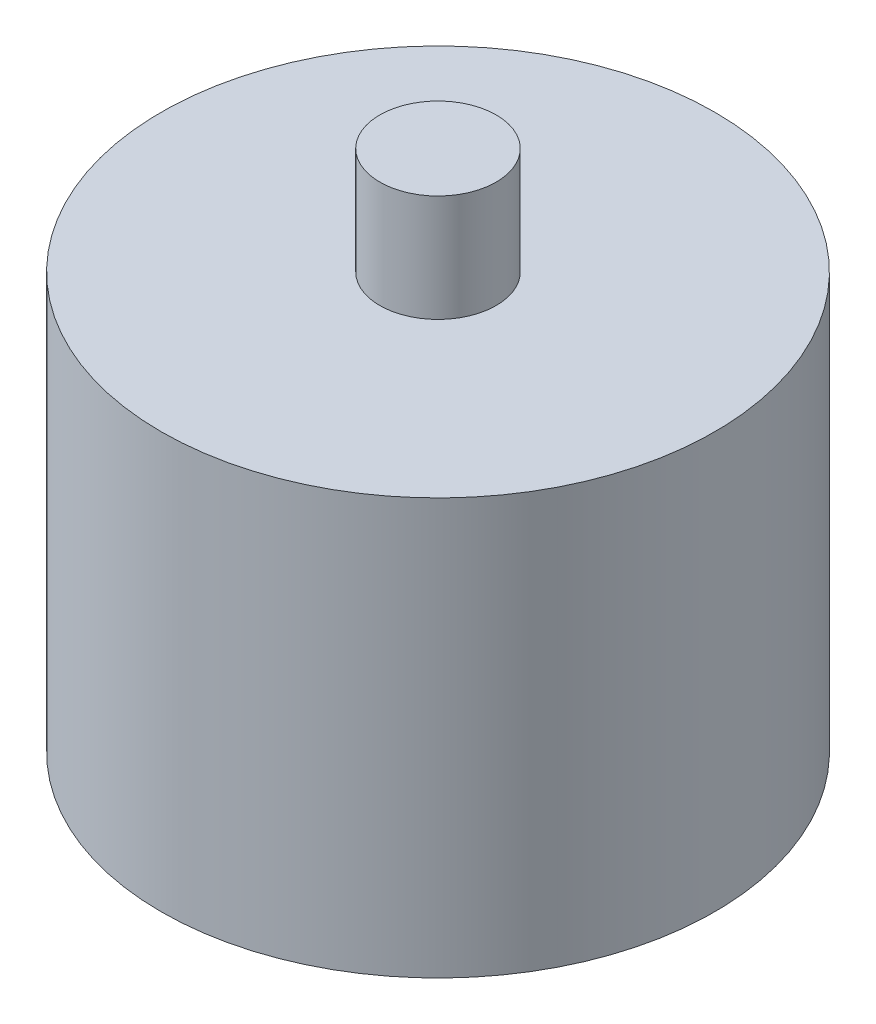
SolidWorks part; units mm, degrees
ref_plane "Front Plane" through (0, 0, 0) normal (0, 0, 1) x (1, 0, 0)
ref_plane "Top Plane" through (0, 0, 0) normal (0, 1, 0) x (1, 0, 0)
ref_plane "Right Plane" through (0, 0, 0) normal (1, 0, 0) x (0, 0, -1)
sketch "Sketch1" plane through (0, 0, 0) normal (0, 0, 1) x (1, 0, 0)
  line L0 (0, 0) -> (0, 33.6333) construction
  line L1 (31.2213, 15.1417) -> (31.2213, 62.0407)
  line L2 (31.2213, 62.0407) -> (6.5659, 62.0407)
  line L3 (6.5659, 62.0407) -> (6.5659, 74.1004)
  line L4 (31.2213, 15.1417) -> (0, 15.1417)
  line L5 (0, 15.1417) -> (0, 74.1004)
  line L6 (0, 74.1004) -> (6.5659, 74.1004)
revolve "Revolve1" add sketch "Sketch1" angle 360 about L0
